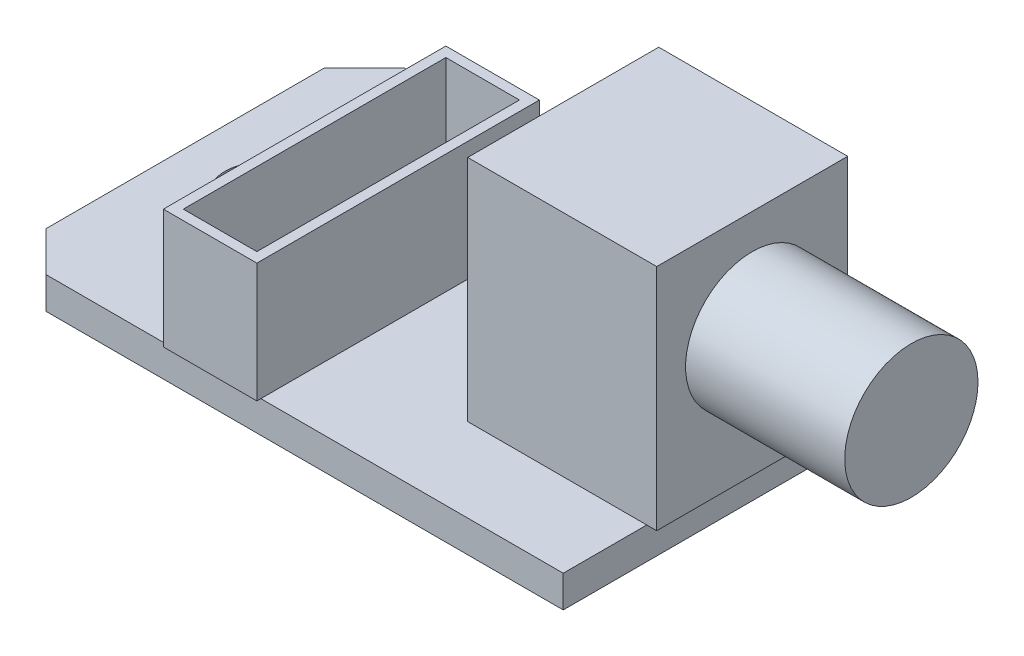
SolidWorks part; units mm, degrees
ref_plane "Front Plane" through (0, 0, 0) normal (0, 0, 1) x (1, 0, 0)
ref_plane "Top Plane" through (0, 0, 0) normal (0, 1, 0) x (1, 0, 0)
ref_plane "Right Plane" through (0, 0, 0) normal (1, 0, 0) x (0, 0, -1)
sketch "Sketch2" plane through (0, 0, 0) normal (0, 1, 0) x (1, 0, 0)
  line L1 (14, -9) -> (-14, -9)
  line L2 (14, -9) -> (14, 9)
  line L3 (14, 9) -> (-14, 9)
  line L4 (-14, -9) -> (-14, 9)
  line L5 (14, -9) -> (-14, 9) construction
  line L6 (14, 9) -> (-14, -9) construction
  point P0 (0, 0)
  dimension "D1" = 28
  dimension "D2" = 18
extrude "Boss-Extrude1" add sketch "Sketch2" along normal blind 1.6
sketch "Sketch4" plane through (14, 0, 0) normal (1, 0, 0) x (0, 0, -1)
  line L0 (-9, 1.6) -> (9, 1.6) construction
  line L1 (-4.8, 13.1) -> (4.8, 13.1)
  line L2 (-4.8, 13.1) -> (-4.8, 1.6)
  line L3 (-4.8, 1.6) -> (4.8, 1.6)
  line L4 (4.8, 13.1) -> (4.8, 1.6)
  line L5 (0, 0) -> (0, 1.6) construction
  line L6 (-9, 0) -> (9, 0) construction
  dimension "D1" = 9.6
  dimension "D2" = 11.5
extrude "Boss-Extrude2" add sketch "Sketch4" along normal blind 0.5 and the other way blind 9
sketch "Sketch5" plane through (14.5, 0, 0) normal (1, 0, 0) x (0, 0, -1)
  circle A0 centre (0, 8) radius 3.35
  dimension "D1" = 8
  dimension "D2" = 6.7
extrude "Boss-Extrude3" add sketch "Sketch5" along normal blind 8
sketch "Sketch6" plane through (0, 1.6, 0) normal (0, 1, 0) x (1, 0, 0)
  line L0 (-14, -9) -> (14, -9) construction
  line L1 (-5.9, 5) -> (-1.2, 5)
  line L2 (-5.9, 5) -> (-5.9, -9.2)
  line L3 (-5.9, -9.2) -> (-1.2, -9.2)
  line L4 (-1.2, 5) -> (-1.2, -9.2)
  line L5 (-14, 9) -> (-14, -9) construction
  dimension "D1" = 14.2
  dimension "D2" = 4.7
  dimension "D3" = 0.2
  dimension "D4" = 8.1
extrude "Boss-Extrude4" add sketch "Sketch6" along normal blind 6
sketch "Sketch7" plane through (0, 1.6, 0) normal (0, 1, 0) x (1, 0, 0)
  line L0 (-14, 9) -> (-14, -9) construction
  circle A0 centre (-10.1, 0) radius 1.9
  dimension "D1" = 3.8
  dimension "D2" = 3.9
extrude "Cut-Extrude1" cut sketch "Sketch7" against normal through all
chamfer "Chamfer1" distance 2 angle 45 2 edges at (-14, 0.8, -9) (-14, 0.8, 9)
sketch "Sketch8" plane through (0, 7.6, 0) normal (0, 1, 0) x (1, 0, 0)
  line L0 (-5.4, 4.5) -> (-5.4, -8.7)
  line L1 (-5.4, -8.7) -> (-1.7, -8.7)
  line L2 (-1.7, -8.7) -> (-1.7, 4.5)
  line L3 (-1.7, 4.5) -> (-5.4, 4.5)
  line L4 (-5.9, 5) -> (-5.9, -9.2)
  line L5 (-5.9, -9.2) -> (-1.2, -9.2)
  line L6 (-1.2, -9.2) -> (-1.2, 5)
  line L7 (-1.2, 5) -> (-5.9, 5)
  line L8 (-5.9, 5) -> (-5.9, -9.2)
  line L9 (-5.9, -9.2) -> (-1.2, -9.2)
  line L10 (-1.2, -9.2) -> (-1.2, 5)
  line L11 (-1.2, 5) -> (-5.9, 5)
  dimension "D1" = 0
  dimension "D2" = 0.5
extrude "Cut-Extrude2" cut sketch "Sketch8" against normal blind 5 contours L2 L3 L0 L1
equation "\"D2@Sketch7\"=2+3.8/2"
